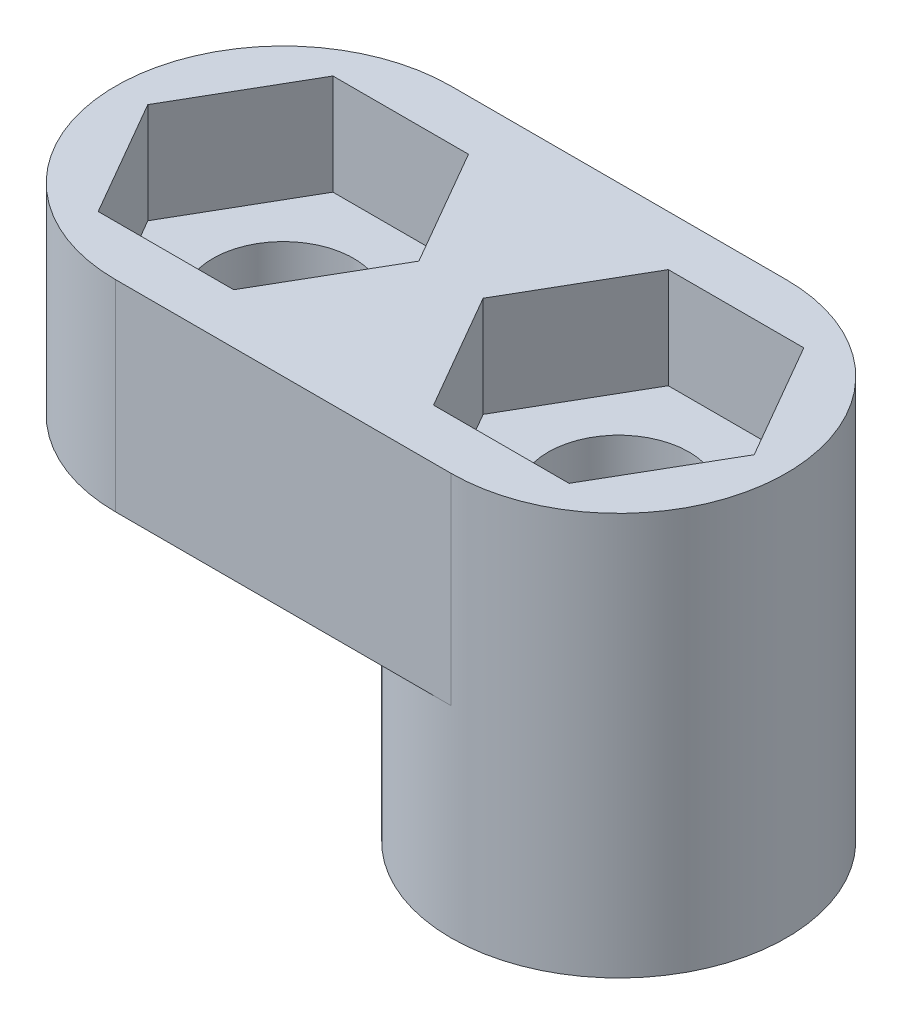
SolidWorks part; units mm, degrees
ref_plane "Front Plane" through (0, 0, 0) normal (0, 0, 1) x (1, 0, 0)
ref_plane "Top Plane" through (0, 0, 0) normal (0, 1, 0) x (1, 0, 0)
ref_plane "Right Plane" through (0, 0, 0) normal (1, 0, 0) x (0, 0, -1)
sketch "Sketch1" plane through (0, 0, 0) normal (0, 1, 0) x (1, 0, 0)
  line L0 (-5, 0) -> (5, 0) construction
  line L1 (-5, 5) -> (5, 5)
  line L2 (-5, -5) -> (5, -5)
  arc A0 (-5, 5) -> (-5, -5) centre (-5, 0) ccw
  arc A1 (5, -5) -> (5, 5) centre (5, 0) ccw
  circle A2 centre (5, 0) radius 2.1
  circle A3 centre (-5, 0) radius 2.1
  point P2 (0, 0)
  dimension "D3" = 4.2
  dimension "D4" = 4.2
  dimension "D1" = 10
  dimension "D2" = 10
extrude "Boss-Extrude1" add sketch "Sketch1" along normal mid plane 6
sketch "Sketch2" plane through (0, 3, 0) normal (0, 1, 0) x (1, 0, 0)
  line L1 (-9.0415, 0) -> (-7.0207, -3.5)
  line L2 (-7.0207, -3.5) -> (-2.9793, -3.5)
  line L3 (-2.9793, -3.5) -> (-0.9585, 0)
  line L4 (-0.9585, 0) -> (-2.9793, 3.5)
  line L5 (-2.9793, 3.5) -> (-7.0207, 3.5)
  line L6 (-7.0207, 3.5) -> (-9.0415, 0)
  line L7 (9.0415, 0) -> (7.0207, 3.5)
  line L8 (7.0207, 3.5) -> (2.9793, 3.5)
  line L9 (2.9793, 3.5) -> (0.9585, 0)
  line L10 (0.9585, 0) -> (2.9793, -3.5)
  line L11 (2.9793, -3.5) -> (7.0207, -3.5)
  line L12 (7.0207, -3.5) -> (9.0415, 0)
  circle A0 centre (-5, 0) radius 3.5 construction
  circle A1 centre (5, 0) radius 3.5 construction
  dimension "D1" = 7
  dimension "D2" = 7
extrude "Cut-Extrude1" cut sketch "Sketch2" against normal blind 3
sketch "Sketch3" plane through (0, -3, 0) normal (0, -1, 0) x (1, 0, 0)
  circle A0 centre (5, 0) radius 2.1
  circle A1 centre (5, 0) radius 5
extrude "Boss-Extrude2" add sketch "Sketch3" along normal blind 6
